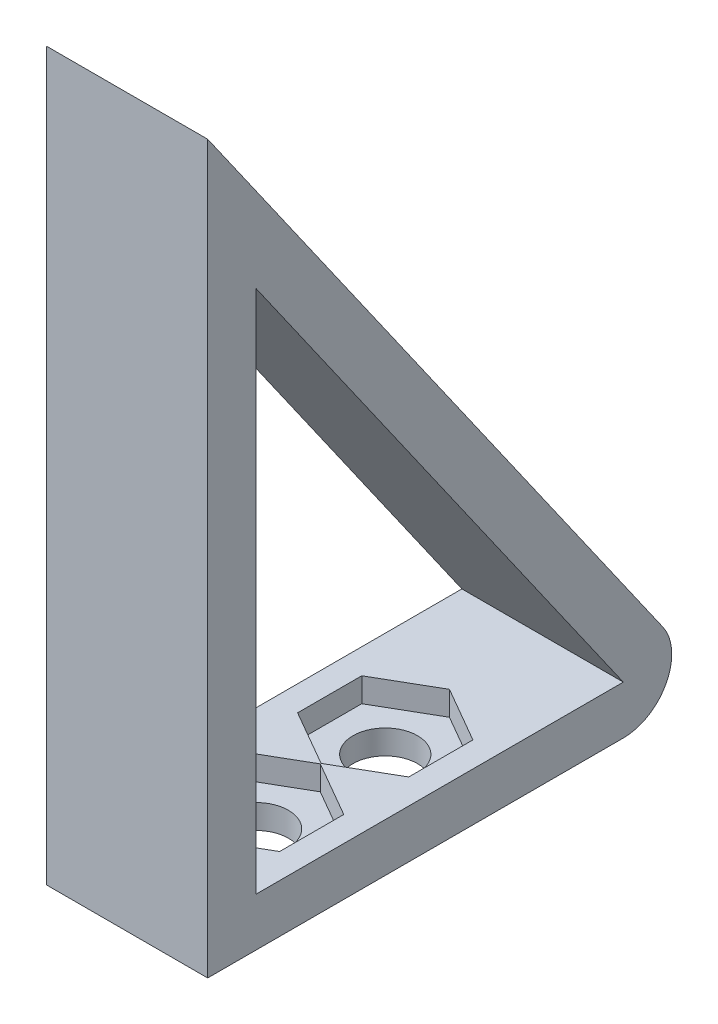
SolidWorks part; units mm, degrees
ref_plane "前视基准面" through (0, 0, 0) normal (0, 0, 1) x (1, 0, 0)
ref_plane "上视基准面" through (0, 0, 0) normal (0, 1, 0) x (1, 0, 0)
ref_plane "右视基准面" through (0, 0, 0) normal (1, 0, 0) x (0, 0, -1)
sketch "Sketch1" plane through (0, 0, 0) normal (1, 0, 0) x (0, 0, -1)
  line L0 (0, 0) -> (0, 45)
  line L1 (0, 45) -> (31.5093, 0)
  line L2 (31.5093, 0) -> (0, 0)
  dimension "D1" = 45
  dimension "D2" = 35
extrude "Boss-Extrude1" add sketch "Sketch1" against normal blind 10
sketch "Sketch2" plane through (0, 0, 0) normal (1, 0, 0) x (0, 0, -1)
  line L0 (0, 45) -> (0, 0) construction
  line L1 (0, 0) -> (31.5093, 0) construction
  line L2 (31.5093, 0) -> (0, 45) construction
  line L3 (25.7464, 3) -> (3, 35.4852)
  line L4 (3, 35.4852) -> (3, 3)
  line L5 (3, 3) -> (25.7464, 3)
  dimension "D1" = 3
extrude "Cut-Extrude1" cut sketch "Sketch2" against normal through all
sketch "Sketch3" plane through (0, 0, 0) normal (0, -1, 0) x (1, 0, 0)
  line L0 (-5, 0.607) -> (-5, -34.9882) construction
  line L1 (-10, 0) -> (-10, -31.5093) construction
  line L2 (-10, 0) -> (0, 0) construction
  circle A0 centre (-5, -8) radius 2
  circle A1 centre (-5, -16) radius 2
  dimension "D2" = 4
  dimension "D3" = 4
  dimension "D1" = 5
  dimension "D4" = 8
  dimension "D5" = 8
extrude "Cut-Extrude2" cut sketch "Sketch3" against normal blind 3
sketch "Sketch4" plane through (0, 3, 0) normal (0, 1, 0) x (1, 0, 0)
  line L0 (-10, 3) -> (-10, 25.7464) construction
  line L1 (-5, 12.025) -> (-1.5575, 14.0125)
  line L2 (-1.5575, 14.0125) -> (-1.5575, 17.9875)
  line L3 (-1.5575, 17.9875) -> (-5, 19.975)
  line L4 (-5, 19.975) -> (-8.4425, 17.9875)
  line L5 (-8.4425, 17.9875) -> (-8.4425, 14.0125)
  line L6 (-8.4425, 14.0125) -> (-5, 12.025)
  line L7 (-5, 11.975) -> (-8.4425, 9.9875)
  line L8 (-8.4425, 9.9875) -> (-8.4425, 6.0125)
  line L9 (-8.4425, 6.0125) -> (-5, 4.025)
  line L10 (-5, 4.025) -> (-1.5575, 6.0125)
  line L11 (-1.5575, 6.0125) -> (-1.5575, 9.9875)
  line L12 (-1.5575, 9.9875) -> (-5, 11.975)
  circle A0 centre (-5, 16) radius 3.4425 construction
  circle A1 centre (-5, 8) radius 3.4425 construction
  dimension "D1" = 7.95
  dimension "D2" = 7.95
extrude "Cut-Extrude3" cut sketch "Sketch4" against normal blind 1.5
fillet "Fillet1" radius 3 1 edges at (-5, 0, -31.5093)
